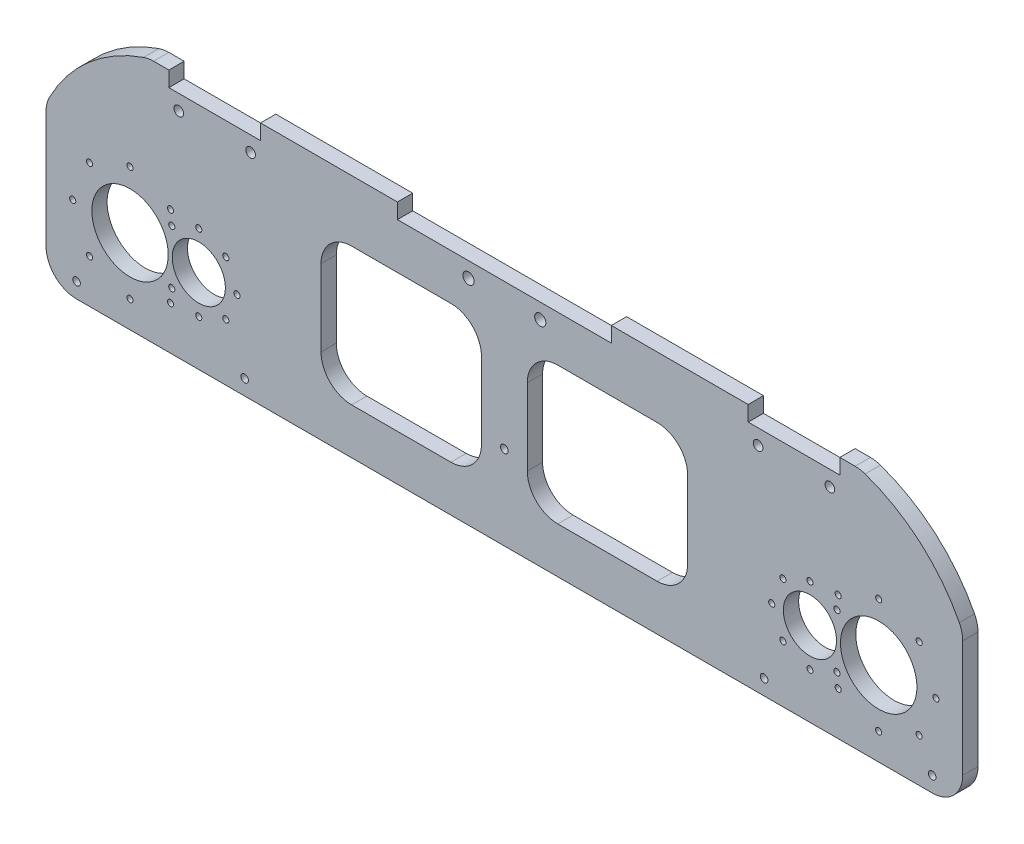
SolidWorks part; units mm, degrees
material "ABS"
ref_plane "Front Plane" through (0, 0, 0) normal (0, 0, 1) x (1, 0, 0)
ref_plane "Top Plane" through (0, 0, 0) normal (0, 1, 0) x (1, 0, 0)
ref_plane "Right Plane" through (0, 0, 0) normal (1, 0, 0) x (0, 0, -1)
sketch "Sketch1" plane through (0, 0, 0) normal (0, 0, 1) x (1, 0, 0)
  line L0 (-145.7836, 66.675) -> (145.7836, 66.675)
  line L1 (-190.5, 26.1817) -> (-190.5, -22.225)
  line L4 (0, 0) -> (0, 100.7987) construction
  line L5 (-177.8, -34.925) -> (177.8, -34.925)
  line L6 (190.5, 26.1817) -> (190.5, -22.225)
  line L7 (-190.5, 34.925) -> (190.5, -34.925) construction
  line L8 (-190.5, -34.925) -> (190.5, 34.925) construction
  arc A0 (177.8, -34.925) -> (190.5, -22.225) centre (177.8, -22.225) ccw
  arc A1 (149.9577, 65.9694) -> (189.0889, 31.9999) centre (127, 0) cw
  circle A2 centre (-127, 0) radius 3.175
  circle A3 centre (127, 0) radius 3.175
  arc A4 (-177.8, -34.925) -> (-190.5, -22.225) centre (-177.8, -22.225) cw
  arc A5 (190.5, 26.1817) -> (189.0889, 31.9999) centre (177.8, 26.1817) ccw
  arc A6 (-149.9577, 65.9694) -> (-189.0889, 31.9999) centre (-127, 0) ccw
  arc A7 (149.9577, 65.9694) -> (145.7836, 66.675) centre (145.7836, 53.975) ccw
  arc A8 (-190.5, 26.1817) -> (-189.0889, 31.9999) centre (-177.8, 26.1817) cw
  arc A9 (-145.7836, 66.675) -> (-149.9577, 65.9694) centre (-145.7836, 53.975) ccw
  point P0 (0, 0)
  point P22 (190.5, 29.0994)
  point P27 (147.8199, 66.675)
  point P30 (-190.5, 29.0994)
  point P33 (-147.8199, 66.675)
  dimension "D3" = 6.35
  dimension "D4" = 6.35
  dimension "D6" = 66.675
  dimension "D7" = 12.7
  dimension "D2" = 381
  dimension "D5" = 12.7
  dimension "D1" = 69.85
  dimension "D8" = 139.7
extrude "Boss-Extrude1" add sketch "Sketch1" along normal mid plane 6.35
sketch "Sketch2" plane through (0, 0, 3.175) normal (0, 0, 1) x (1, 0, 0)
  line L0 (-127, 0) -> (-207.737, 0) construction
  line L4 (0, 0) -> (0, 93.9723) construction
  circle A0 centre (-127, 0) radius 11.049
  circle A1 centre (-155.575, 0) radius 15.875
  circle A2 centre (127, 0) radius 15.875 construction
  circle A3 centre (155.575, 0) radius 23.8125 construction
  circle A4 centre (-155.575, 0) radius 23.8125 construction
  circle A5 centre (-127, 0) radius 15.875 construction
  circle A6 centre (-155.575, 23.8125) radius 1.27
  circle A7 centre (-138.737, 16.838) radius 1.27
  circle A8 centre (-131.7625, 0) radius 1.27 [skipped]
  circle A9 centre (-138.737, -16.838) radius 1.27
  circle A10 centre (-155.575, -23.8125) radius 1.27
  circle A11 centre (-172.413, -16.838) radius 1.27
  circle A12 centre (-179.3875, 0) radius 1.27
  circle A13 centre (-172.413, 16.838) radius 1.27
  circle A14 centre (-127, 15.875) radius 1.27
  circle A15 centre (-115.7747, 11.2253) radius 1.27
  circle A16 centre (-111.125, 0) radius 1.27
  circle A17 centre (-115.7747, -11.2253) radius 1.27
  circle A18 centre (-127, -15.875) radius 1.27
  circle A19 centre (-138.2253, -11.2253) radius 1.27
  circle A20 centre (138.2253, 11.2253) radius 1.27
  circle A21 centre (-138.2253, 11.2253) radius 1.27
  circle A22 centre (-142.875, 0) radius 1.27 [skipped]
  circle A23 centre (138.2253, -11.2253) radius 1.27
  circle A24 centre (127, -15.875) radius 1.27
  circle A25 centre (115.7747, -11.2253) radius 1.27
  circle A26 centre (111.125, 0) radius 1.27
  circle A27 centre (115.7747, 11.2253) radius 1.27
  circle A28 centre (127, 15.875) radius 1.27
  circle A29 centre (172.413, 16.838) radius 1.27
  circle A30 centre (179.3875, 0) radius 1.27
  circle A31 centre (172.413, -16.838) radius 1.27
  circle A32 centre (155.575, -23.8125) radius 1.27
  circle A33 centre (138.737, -16.838) radius 1.27
  circle A34 centre (138.737, 16.838) radius 1.27
  circle A35 centre (155.575, 23.8125) radius 1.27
  circle A36 centre (155.575, 0) radius 15.875
  circle A37 centre (127, 0) radius 11.049
  dimension "D2" = 28.575
  dimension "D3" = 31.75
  dimension "D4" = 31.75
  dimension "D5" = 47.625
  dimension "D6" = 2.54
  dimension "D1" = 22.098
  dimension "D8" = 2.54
  dimension "D7" = 8
  dimension "D9" = 8
extrude "Cut-Extrude1" cut sketch "Sketch2" against normal through all
sketch "Sketch3" plane through (0, 0, 3.175) normal (0, 0, 1) x (1, 0, 0)
  line L0 (0, 0) -> (0, 109.3078) construction
  line L1 (145.7836, 66.675) -> (-145.7836, 66.675) construction
  line L2 (-101.3336, 66.675) -> (-139.4336, 66.675)
  line L3 (-101.3336, 66.675) -> (-101.3336, 60.325)
  line L4 (-101.3336, 60.325) -> (-139.4336, 60.325)
  line L5 (-139.4336, 66.675) -> (-139.4336, 60.325)
  line L6 (139.4336, 66.675) -> (139.4336, 60.325)
  line L7 (101.3336, 60.325) -> (139.4336, 60.325)
  line L8 (101.3336, 66.675) -> (101.3336, 60.325)
  line L9 (101.3336, 66.675) -> (139.4336, 66.675)
  line L11 (44.45, 60.325) -> (-44.45, 60.325)
  line L12 (44.45, 60.325) -> (44.45, 66.675)
  line L13 (44.45, 66.675) -> (-44.45, 66.675)
  line L14 (-44.45, 60.325) -> (-44.45, 66.675)
  line L15 (44.45, 60.325) -> (-44.45, 66.675) construction
  line L16 (44.45, 66.675) -> (-44.45, 60.325) construction
  point P13 (0, 63.5)
  dimension "D1" = 6.35
  dimension "D2" = 38.1
  dimension "D3" = 6.35
  dimension "D4" = 6.35
  dimension "D5" = 88.9
extrude "Cut-Extrude4" cut sketch "Sketch3" against normal through all
sketch "Sketch4" plane through (0, 0, 3.175) normal (0, 0, 1) x (1, 0, 0)
  line L0 (0, 93.6628) -> (0, -75.0769) construction
  line L1 (101.3336, 66.675) -> (44.45, 66.675) construction
  line L2 (-63.5, 41.275) -> (-22.225, 41.275)
  line L3 (-76.2, 28.575) -> (-76.2, -3.175)
  line L4 (-63.5, -15.875) -> (-22.225, -15.875)
  line L5 (76.2, 28.575) -> (76.2, -3.175)
  line L6 (-76.2, 41.275) -> (76.2, -15.875) construction
  line L7 (-76.2, -15.875) -> (76.2, 41.275) construction
  line L8 (-177.8, -34.925) -> (177.8, -34.925) construction
  line L9 (-9.525, 28.575) -> (-9.525, -3.175)
  line L10 (9.525, 28.575) -> (9.525, -3.175)
  line L11 (22.225, 41.275) -> (63.5, 41.275)
  line L12 (22.225, -15.875) -> (63.5, -15.875)
  arc A0 (63.5, 41.275) -> (76.2, 28.575) centre (63.5, 28.575) cw
  arc A1 (76.2, -3.175) -> (63.5, -15.875) centre (63.5, -3.175) cw
  arc A2 (-63.5, -15.875) -> (-76.2, -3.175) centre (-63.5, -3.175) cw
  arc A3 (-63.5, 41.275) -> (-76.2, 28.575) centre (-63.5, 28.575) ccw
  arc A4 (22.225, 41.275) -> (9.525, 28.575) centre (22.225, 28.575) ccw
  arc A5 (22.225, -15.875) -> (9.525, -3.175) centre (22.225, -3.175) cw
  arc A6 (-22.225, -15.875) -> (-9.525, -3.175) centre (-22.225, -3.175) ccw
  arc A7 (-22.225, 41.275) -> (-9.525, 28.575) centre (-22.225, 28.575) cw
  point P2 (0, 12.7)
  point P30 (9.525, 41.275)
  point P33 (9.525, -15.875)
  dimension "D4" = 12.7
  dimension "D7" = 12.7
  dimension "D1" = 25.4
  dimension "D2" = 19.05
  dimension "D3" = 152.4
  dimension "D5" = 9.525
  dimension "D6" = 9.525
extrude "Cut-Extrude5" cut sketch "Sketch4" against normal through all
sketch "Sketch5" plane through (0, 0, 3.175) normal (0, 0, 1) x (1, 0, 0)
  line L0 (-139.4336, 60.325) -> (-101.3336, 60.325) construction
  line L1 (-120.3836, 60.325) -> (-120.3836, 34.1975) construction
  line L2 (0, 75.8339) -> (0, -69.5106) construction
  circle A0 centre (-135.3061, 53.975) radius 2.0035
  circle A1 centre (-105.4611, 53.975) radius 2.0035
  circle A2 centre (105.4611, 53.975) radius 2.0035
  circle A3 centre (135.3061, 53.975) radius 2.0035
  circle A4 centre (-14.9225, 53.975) radius 2.3325
  circle A5 centre (14.9225, 53.975) radius 2.3325
  dimension "D1" = 6.35
  dimension "D2" = 14.9225
  dimension "D3" = 14.9225
extrude "Cut-Extrude6" cut sketch "Sketch5" against normal through all
sketch "Sketch6" plane through (0, 0, 3.175) normal (0, 0, 1) x (1, 0, 0)
  line L0 (0, 26.7131) -> (0, -52.4222) construction
  line L1 (-177.8, -34.925) -> (177.8, -34.925) construction
  circle A0 centre (-177.8, -28.575) radius 1.5875
  circle A1 centre (-107.95, -28.575) radius 1.5875
  circle A2 centre (107.95, -28.575) radius 1.5875
  circle A3 centre (177.8, -28.575) radius 1.5875
  dimension "D1" = 3.175
  dimension "D5" = 3.175
  dimension "D2" = 177.8
  dimension "D3" = 6.35
  dimension "D4" = 107.95
extrude "Cut-Extrude7" cut sketch "Sketch6" against normal through all
sketch "Sketch7" plane through (0, 0, 3.175) normal (0, 0, 1) x (1, 0, 0)
  circle A0 centre (0, 0) radius 1.5875
  dimension "D1" = 3.175
extrude "Cut-Extrude8" cut sketch "Sketch7" against normal through all
